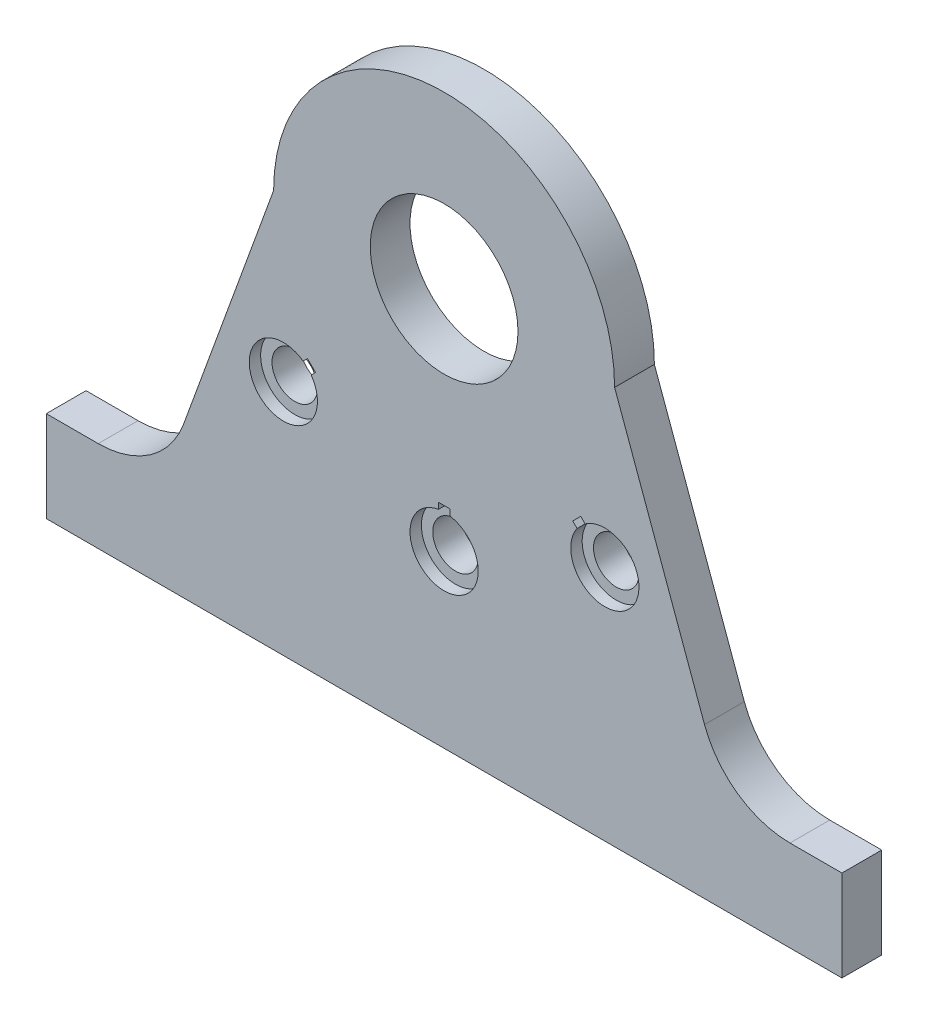
SolidWorks part; units mm, degrees
ref_plane "Front Plane" through (0, 0, 0) normal (0, 0, 1) x (1, 0, 0)
ref_plane "Top Plane" through (0, 0, 0) normal (0, 1, 0) x (1, 0, 0)
ref_plane "Right Plane" through (0, 0, 0) normal (1, 0, 0) x (0, 0, -1)
sketch "Sketch1" plane through (0, 0, 0) normal (0, 0, 1) x (1, 0, 0)
  line L0 (-15, 0) -> (-22.9113, -21.7362)
  line L1 (-30.4289, -27) -> (-35, -27)
  line L2 (-35, -27) -> (-35, -35)
  line L3 (-35, -35) -> (35, -35)
  line L4 (35, -35) -> (35, -27)
  line L5 (35, -27) -> (30.4289, -27)
  line L6 (22.9113, -21.7362) -> (15, 0)
  line L7 (-15, 0) -> (-15, -22.2563) construction
  line L8 (-15, -22.2563) -> (15, -22.2563) construction
  line L9 (15, -22.2563) -> (15, 0) construction
  arc A0 (15, 0) -> (-15, 0) centre (0, 0) ccw
  circle A1 centre (0, 0) radius 6.5
  arc A2 (-30.4289, -27) -> (-22.9113, -21.7362) centre (-30.4289, -19) ccw
  arc A3 (30.4289, -27) -> (22.9113, -21.7362) centre (30.4289, -19) cw
  point P1 (34.9679, -30.2563)
  dimension "D1" = 13
  dimension "D2" = 30
  dimension "D5" = 8
  dimension "D8" = 35
  dimension "D3" = 20
  dimension "D4" = 20
  dimension "D6" = 8
  dimension "D7" = 20
extrude "Boss-Extrude1" add sketch "Sketch1" along normal blind 3.5
sketch "Sketch2" plane through (0, 0, 3.5) normal (0, 0, 1) x (1, 0, 0)
  line L0 (-14.1421, -14.1421) -> (0, 0) construction
  line L1 (0, 0) -> (14.1421, -14.1421) construction
  line L2 (0, 0) -> (0, -35) construction
  line L3 (-35, -35) -> (35, -35) construction
  arc A0 (14.1421, -14.1421) -> (-14.1421, -14.1421) centre (0, 0) cw construction
  circle A1 centre (-14.1421, -14.1421) radius 2
  circle A2 centre (0, -20) radius 2
  circle A3 centre (14.1421, -14.1421) radius 2
  point P3 (0, -20)
  dimension "D2" = 4
  dimension "D1" = 20
extrude "Cut-Extrude1" cut sketch "Sketch2" against normal blind 10 contours A1
sketch "Sketch3" plane through (0, 0, 0) normal (0, 0, -1) x (-1, 0, 0)
  line L0 (-14.1421, -14.1421) -> (0, 0) construction
  line L2 (-12.404, -11.6969) -> (-12.0208, -11.3137)
  line L3 (-12.0208, -11.3137) -> (-11.3137, -12.0208)
  line L4 (-11.6969, -12.404) -> (-11.3137, -12.0208)
  line L7 (0, -20) -> (0, 0) construction
  line L8 (-0.5, -17.042) -> (-0.5, -16.5)
  line L9 (-0.5, -16.5) -> (0.5, -16.5)
  line L10 (0.5, -17.042) -> (0.5, -16.5)
  line L11 (0, -17) -> (0.5, -16.5) construction
  line L12 (-0.5, -16.5) -> (0, -17) construction
  line L13 (14.1421, -14.1421) -> (0, 0) construction
  line L14 (11.6969, -12.404) -> (11.3137, -12.0208)
  line L15 (11.3137, -12.0208) -> (12.0208, -11.3137)
  line L16 (12.404, -11.6969) -> (12.0208, -11.3137)
  arc A1 (-12.404, -11.6969) -> (-11.6969, -12.404) centre (-14.1421, -14.1421) ccw
  arc A3 (-0.5, -17.042) -> (0.5, -17.042) centre (0, -20) ccw
  arc A5 (11.6969, -12.404) -> (12.404, -11.6969) centre (14.1421, -14.1421) ccw
  point P4 (-14.1421, -11.1421)
  point P6 (-11.227, -12.1416)
  point P10 (0, 0)
  point P11 (-11.6673, -11.6673)
  point P12 (-11.3434, -11.9818)
  point P13 (-9.7902, -8.6594)
  point P14 (-9.1752, -9.2096)
  point P15 (0, 0)
  point P20 (0, -17)
  point P26 (0, -16.5)
  point P27 (0, 0)
  point P28 (0, -20)
  point P30 (0, -20)
  point P34 (14.1421, -14.1421)
  point P39 (0.5, 0)
  point P40 (11.6673, -11.6673)
  point P41 (-14.1421, -11.1421)
  point P42 (0, 0)
  dimension "D1" = 6
  dimension "D4" = 6
  dimension "D7" = 6
  dimension "D2" = 0.542
  dimension "D3" = 1
  dimension "D5" = 1
  dimension "D6" = 0.542
  dimension "D8" = 1
extrude "Cut-Extrude2" cut sketch "Sketch3" along normal blind 1 from surface at -3.5 contours A1 L4 L3 L2
sketch "Sketch4" plane through (0, 0, 3.5) normal (0, 0, 1) x (1, 0, 0)
  line L0 (0, 0) -> (14.1421, -14.1421)
  circle A0 centre (0, 0) radius 10
  dimension "D1" = 20
